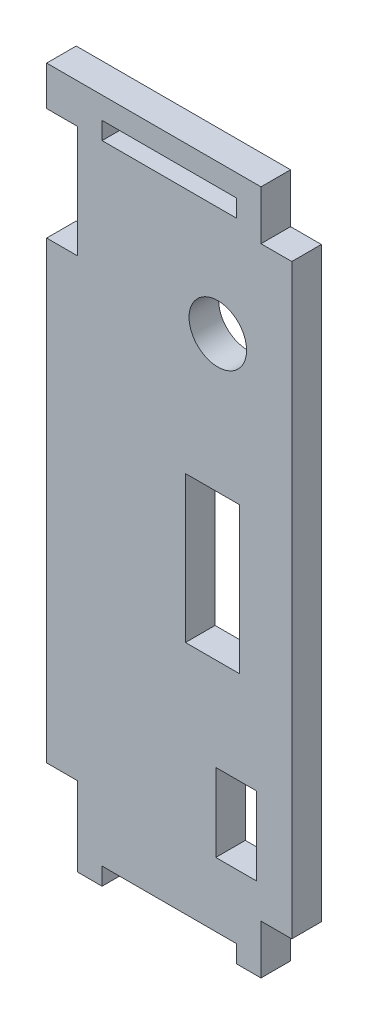
SolidWorks part; units mm, degrees
ref_plane "Front Plane" through (0, 0, 0) normal (0, 0, 1) x (1, 0, 0)
ref_plane "Top Plane" through (0, 0, 0) normal (0, 1, 0) x (1, 0, 0)
ref_plane "Right Plane" through (0, 0, 0) normal (1, 0, 0) x (0, 0, -1)
sketch "Sketch1" plane through (0, 0, 0) normal (0, 0, 1) x (1, 0, 0)
  line L0 (3.175, 53.213) -> (0, 53.213) construction
  line L1 (3.175, 6.35) -> (0, 6.35) construction
  line L2 (3.175, 53.213) -> (0, 53.213)
  line L3 (3.175, 6.35) -> (0, 6.35)
  line L4 (0, 53.213) -> (0, 6.35)
  line L5 (3.175, 6.35) -> (3.175, -1.8034)
  line L6 (3.175, -1.8034) -> (22.098, -1.8034)
  line L7 (22.098, -1.8034) -> (22.098, 3.2766)
  line L8 (22.098, 3.2766) -> (25.273, 3.2766)
  line L9 (25.273, 3.2766) -> (25.273, 63.754)
  line L10 (25.273, 63.754) -> (22.098, 63.754)
  line L11 (22.098, 63.754) -> (22.098, 68.834)
  line L12 (22.098, 68.834) -> (3.175, 68.834)
  line L13 (3.175, 68.834) -> (3.175, 53.213)
  line L14 (3.175, 64.77) -> (0, 64.77) construction
  line L15 (5.715, -1.8034) -> (5.715, 0)
  line L16 (5.715, 64.77) -> (19.558, 64.77)
  line L17 (5.715, 64.77) -> (5.715, 66.5734)
  line L18 (5.715, 66.5734) -> (19.558, 66.5734)
  line L19 (19.558, 64.77) -> (19.558, 66.5734)
  line L20 (5.715, 0) -> (19.558, 0)
  line L21 (19.558, 0) -> (19.558, -1.8034)
  line L22 (3.175, 68.834) -> (0, 68.834)
  line L23 (0, 68.834) -> (0, 64.77)
  line L24 (0, 64.77) -> (3.175, 64.77)
  line B0 (21.6154, 6.6294) -> (21.6154, 14.6685)
  line B1 (19.9009, 24.257) -> (19.9009, 39.3446)
  line B2 (17.4371, 14.6685) -> (21.6154, 14.6685)
  line B3 (17.4371, 6.6294) -> (17.4371, 14.6685)
  line B4 (17.4371, 6.6294) -> (21.6154, 6.6294)
  line B5 (19.9009, 24.257) -> (14.3129, 24.257)
  line B6 (14.3129, 24.257) -> (14.3129, 39.3446)
  line B7 (19.9009, 39.3446) -> (14.3129, 39.3446)
  line B8 (22.098, 46.863) -> (22.098, 84.963)
  line B9 (10.7188, 0) -> (17.018, 0)
  circle B10 centre (17.6467, 53.4861) radius 2.9655
  dimension "D1" = 18.923
  dimension "D2" = 5.08
  dimension "D3" = 5.08
  dimension "D4" = 4.064
  dimension "D5" = 1.8034
  dimension "D6" = 2.54
  dimension "D7" = 2.54
  dimension "D8" = 2.54
  dimension "D9" = 2.54
sketch_block_instance "RPIHolePlacement-1"
sketch_block "RPIHolePlacement"
extrude "Boss-Extrude1" add sketch "Sketch1" along normal blind 3.048
